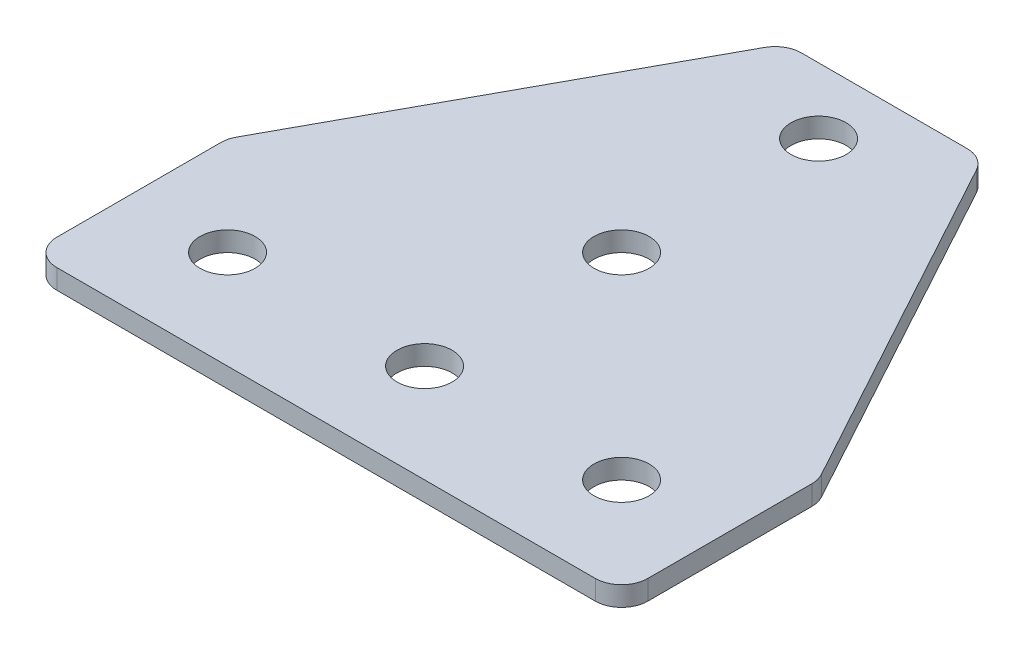
SolidWorks part; units mm, degrees
material "1060 合金"
ref_plane "正面" through (0, 0, 0) normal (0, 0, 1) x (1, 0, 0)
ref_plane "平面" through (0, 0, 0) normal (0, 1, 0) x (1, 0, 0)
ref_plane "右側面" through (0, 0, 0) normal (1, 0, 0) x (0, 0, -1)
sketch "ｽｹｯﾁ1" plane through (0, 0, 0) normal (0, 1, 0) x (1, 0, 0)
  line L0 (0, 0) -> (45, 0)
  line L1 (45, 0) -> (45, 15)
  line L2 (45, 15) -> (30, 42.5)
  line L3 (30, 42.5) -> (15, 42.5)
  line L4 (15, 42.5) -> (0, 15)
  line L5 (0, 15) -> (0, 0)
  line L6 (22.5, 0) -> (22.5, 42.5) construction
  line L7 (45, 7.5) -> (0, 7.5) construction
  circle A0 centre (7.5, 7.5) radius 2.1
  circle A1 centre (37.5, 7.5) radius 2.1
  circle A2 centre (22.5, 7.5) radius 2.1
  circle A3 centre (22.5, 37.5) radius 2.1
  circle A6 centre (22.5, 22.5) radius 2.1
  dimension "D3" = 4.2
  dimension "D4" = 7.5
  dimension "D5" = 5
  dimension "D6" = 7.5
  dimension "D7" = 15
  dimension "D9" = 15
  dimension "D1" = 15
  dimension "D2" = 15
extrude "ﾎﾞｽ - 押し出し1" add sketch "ｽｹｯﾁ1" along normal blind 1.5
fillet "ﾌｨﾚｯﾄ1" radius 2 6 edges at (0, 0.75, -15) (0, 0.75, 0) (45, 0.75, 0) (45, 0.75, -15) (30, 0.75, -42.5) (15, 0.75, -42.5)
